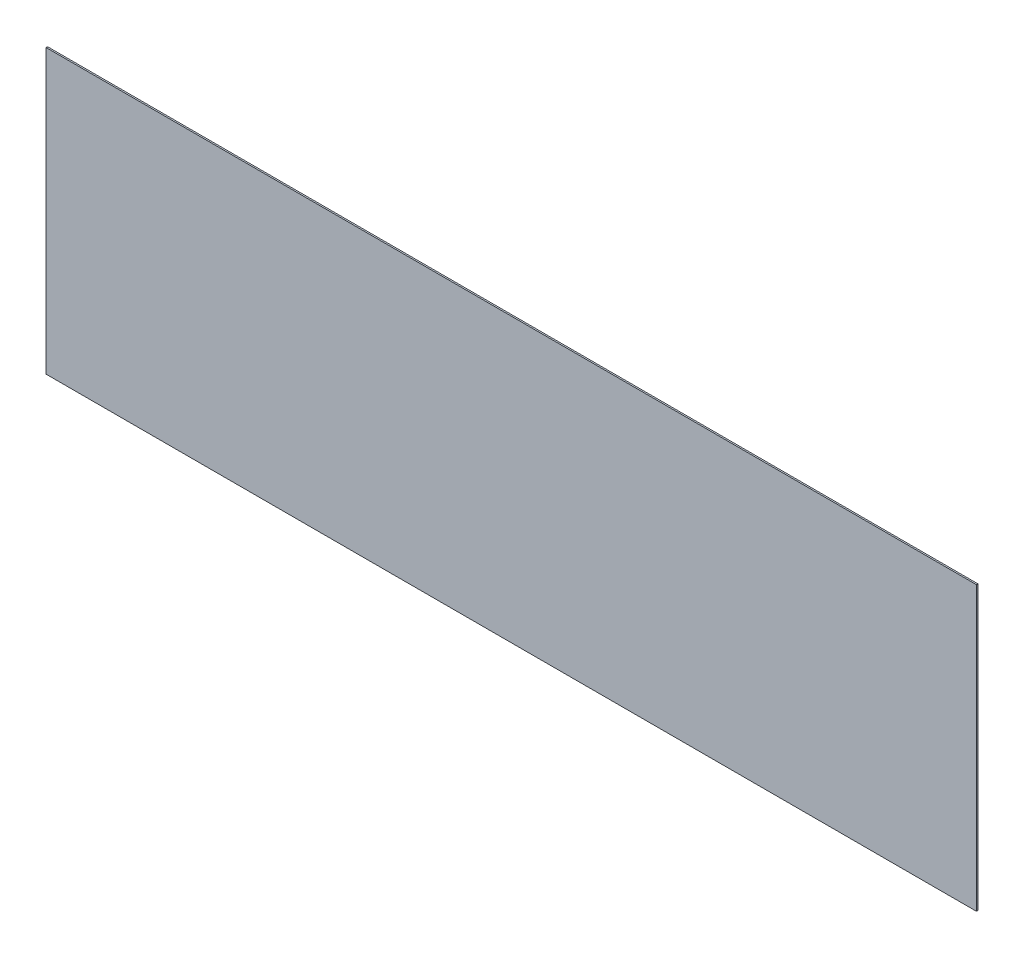
SolidWorks part; units mm, degrees
material "ABS"
ref_plane "Front Plane" through (0, 0, 0) normal (0, 0, 1) x (1, 0, 0)
ref_plane "Top Plane" through (0, 0, 0) normal (0, 1, 0) x (1, 0, 0)
ref_plane "Right Plane" through (0, 0, 0) normal (1, 0, 0) x (0, 0, -1)
sketch "Sketch1" plane through (0, 0, 0) normal (0, 0, 1) x (1, 0, 0)
  line L0 (0, 380) -> (0, 0) construction
  line L1 (-1250, 380) -> (1250, 380)
  line L2 (-1250, 380) -> (-1250, -380)
  line L3 (-1250, -380) -> (1250, -380)
  line L4 (1250, 380) -> (1250, -380)
  line L5 (0, 0) -> (0, -380) construction
  dimension "D1" = 2500
  dimension "D2" = 760
extrude "Boss-Extrude1" add sketch "Sketch1" along normal blind 4
